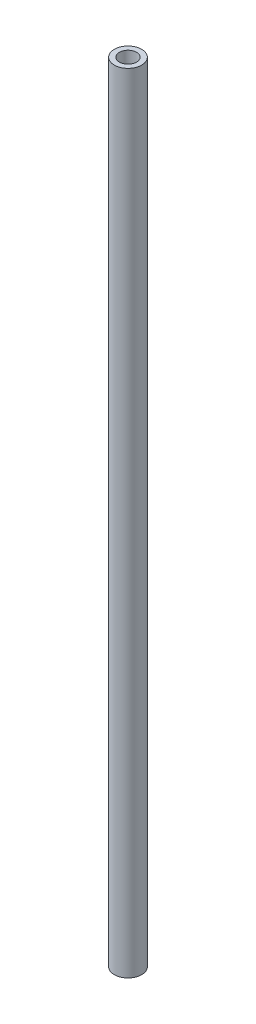
SolidWorks part; units mm, degrees
ref_plane "Płaszczyzna przednia" through (0, 0, 0) normal (0, 0, 1) x (1, 0, 0)
ref_plane "Płaszczyzna górna" through (0, 0, 0) normal (0, 1, 0) x (1, 0, 0)
ref_plane "Płaszczyzna prawa" through (0, 0, 0) normal (1, 0, 0) x (0, 0, -1)
sketch "Szkic1" plane through (0, 0, 0) normal (0, 1, 0) x (1, 0, 0)
  circle A0 centre (0, 0) radius 2.5
  circle A1 centre (0, 0) radius 4
  dimension "D1" = 5
  dimension "D2" = 8
extrude "Dodanie-wyciągnięcie1" add sketch "Szkic1" along normal blind 230
